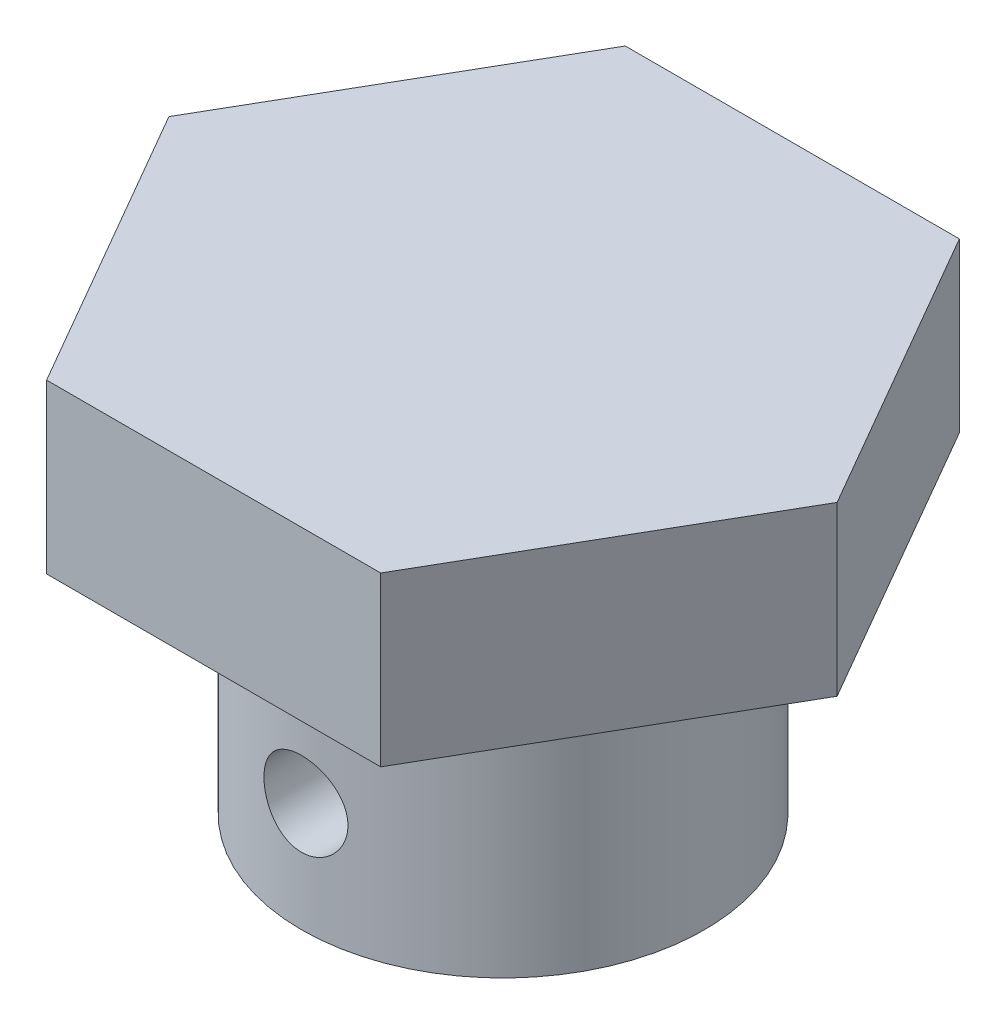
SolidWorks part; units mm, degrees
ref_plane "Alzado" through (0, 0, 0) normal (0, 0, 1) x (1, 0, 0)
ref_plane "Planta" through (0, 0, 0) normal (0, 1, 0) x (1, 0, 0)
ref_plane "Vista lateral" through (0, 0, 0) normal (1, 0, 0) x (0, 0, -1)
sketch "Croquis1" plane through (0, 0, 0) normal (1, 0, 0) x (0, 0, -1)
  line L0 (0, 0) -> (0, 19394.6636) construction
  line L3 (0, 0) -> (-6, 0)
  line L4 (-6, 0) -> (-6, 8)
  line L5 (-6, 8) -> (0, 8)
  line L6 (0, 8) -> (0, 0)
  dimension "D2" = 8
  dimension "D3" = 6
revolve "Revolución1" add sketch "Croquis1" angle 360 about L0
sketch "Croquis2" plane through (0, 8, 0) normal (0, 1, 0) x (1, 0, 0)
  line L1 (-9.95, 0) -> (-4.975, -8.617)
  line L2 (-4.975, -8.617) -> (4.975, -8.617)
  line L3 (4.975, -8.617) -> (9.95, 0)
  line L4 (9.95, 0) -> (4.975, 8.617)
  line L5 (4.975, 8.617) -> (-4.975, 8.617)
  line L6 (-4.975, 8.617) -> (-9.95, 0)
  circle A1 centre (0, 0) radius 9.95 construction
  point P0 (0, 0)
  dimension "D1" = 19.9
extrude "Saliente-Extruir1" add sketch "Croquis2" along normal blind 5
fillet "Redondeo4" radius 1.5 1 edges at (0, 8, -6)
sketch "Sketch1" plane through (0, 0, 0) normal (1, 0, 0) x (0, 0, -1)
  line L0 (-6, 3.25) -> (0, 3.25) construction
  line L2 (0, 3.25) -> (0, 0) construction
  line L3 (-6, 0) -> (6, 0) construction
  line L4 (-6, 6.5) -> (-6, 0) construction
  point P2 (0, 0)
  point P3 (0, 0)
  point P7 (0, 0)
  point P8 (0, 0)
sketch "Sketch6" plane through (0, 0, 0) normal (0, -1, 0) x (1, 0, 0)
  circle A0 centre (0, 0) radius 4
  dimension "D1" = 8
extrude "Cut-Extrude1" cut sketch "Sketch6" against normal blind 10 contours A0
hole_wizard "Tap Drill for M3x0.5 Tap1" positions "3DSketch3" profile "Sketch5" hole size "M3x0.5" standard "ANSI Metric" end condition through all
sketch3d "3DSketch3"
  line L0 (0, 3.25, 6) -> (0, 3.25, 0) construction
  point P0 (0, 3.25, 6)
sketch "Sketch5" plane through (0, 3.25, 6) normal (1, 0, 0) x (0, -1, 0)
  line L0 (0, 0) -> (0, 14.617)
  line L1 (0, 14.617) -> (1.25, 14.617)
  line L2 (1.25, 14.617) -> (1.25, 0)
  line L5 (1.25, 0) -> (0, 0)
  line L11 (0, -6.35) -> (0, 107.95) construction
  dimension "Thru Hole Dia." = 2.5
  dimension "Thru Hole Depth" = 14.617
